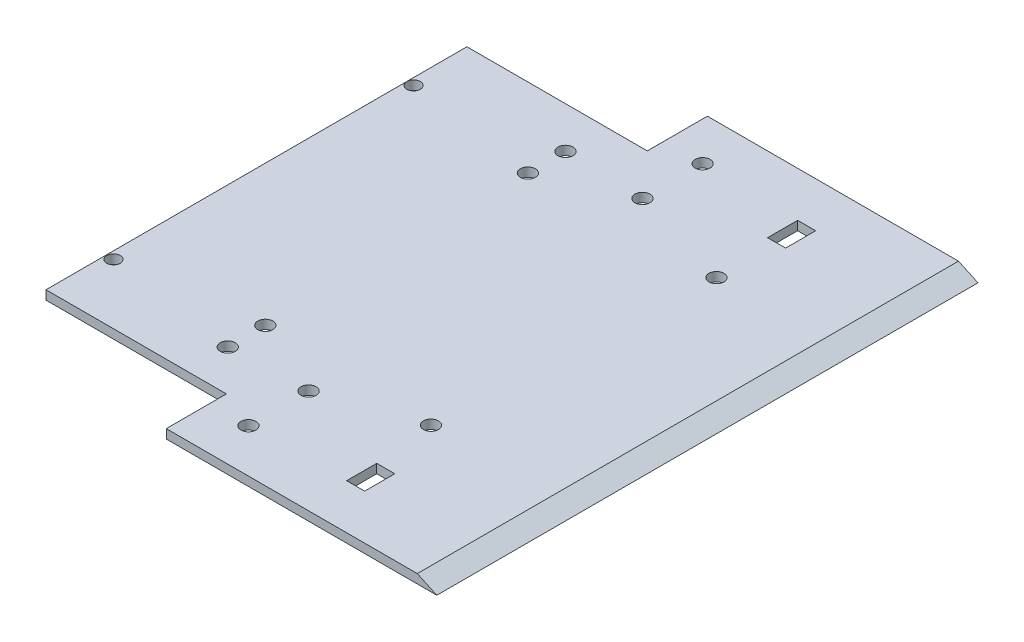
SolidWorks part; units mm, degrees
ref_plane "Front Plane" through (0, 0, 0) normal (0, 0, 1) x (1, 0, 0)
ref_plane "Top Plane" through (0, 0, 0) normal (0, 1, 0) x (1, 0, 0)
ref_plane "Right Plane" through (0, 0, 0) normal (1, 0, 0) x (0, 0, -1)
sketch "Esquisse1" plane through (0, 0, 0) normal (0, 1, 0) x (1, 0, 0)
  line L0 (-75, 0) -> (75, 0) construction
  line L1 (75, -90) -> (-75, -90)
  line L2 (75, -90) -> (75, 90)
  line L3 (75, 90) -> (-75, 90)
  line L4 (-75, -90) -> (-75, 90)
  line L5 (75, -90) -> (-75, 90) construction
  line L6 (75, 90) -> (-75, -90) construction
  line L7 (-75, 90) -> (-15, 90)
  line L8 (-75, 90) -> (-75, 70)
  line L9 (-75, 70) -> (-15, 70)
  line L10 (-15, 90) -> (-15, 70)
  line L11 (-75, -70) -> (-15, -70)
  line L12 (-15, -90) -> (-15, -70)
  line L13 (-75, -90) -> (-15, -90)
  line L14 (-75, -90) -> (-75, -70)
  line L15 (-2.1116, 55.5) -> (-2.1615, -75.5) construction
  line L16 (45, 90) -> (45, -90) construction
  line L17 (45, 0) -> (75, 0) construction
  line L18 (45, 0) -> (75, 90) construction
  line L19 (45, 90) -> (75, 0) construction
  line L20 (75, 0) -> (45, -90) construction
  line L21 (75, -90) -> (45, 0) construction
  line L22 (33, 90) -> (33, 70) construction
  line L23 (33, 70) -> (75, 70) construction
  line L24 (36, -65) -> (36, -75)
  line L25 (36, 65) -> (30, 65)
  line L26 (36, 65) -> (36, 75)
  line L27 (36, 75) -> (30, 75)
  line L28 (30, 65) -> (30, 75)
  line L29 (36, 65) -> (30, 75) construction
  line L30 (36, 75) -> (30, 65) construction
  line L31 (36, -75) -> (30, -75)
  line L32 (30, -65) -> (30, -75)
  line L33 (36, -65) -> (30, -65)
  circle A0 centre (-2.1116, 55.5) radius 2.5
  circle A1 centre (-2.1116, 75.5) radius 2.5
  circle A2 centre (-2.1615, -55.5) radius 2.5
  circle A3 centre (-2.1615, -75.5) radius 2.5
  circle A7 centre (33, 45) radius 2.5
  circle A8 centre (28.0394, -45) radius 2.5005
  circle A15 centre (-28.4765, 56.25) radius 2.5
  circle A16 centre (-28.4765, 43.75) radius 2.5
  circle A17 centre (-72.731, 50) radius 2.25
  circle A18 centre (-28.2769, -56.2709) radius 2.5
  circle A19 centre (-28.2769, -43.7709) radius 2.5
  circle A20 centre (-72.5314, -50.0209) radius 2.25
  point P0 (0, 0)
  dimension "D5" = 5
  dimension "D6" = 5
  dimension "D8" = 5
  dimension "D9" = 20
  dimension "D1" = 150
  dimension "D2" = 180
  dimension "D3" = 60
  dimension "D4" = 20
  dimension "D7" = 30
  dimension "D10" = 42
  dimension "D11" = 10
  dimension "D12" = 6
extrude "Boss.-Extru.1" add sketch "Esquisse1" along normal blind 3 contours L12 L1 L2 L3 L10 L9 L4 L11
sketch "Esquisse4" plane through (0, 0, 90) normal (0, 0, 1) x (1, 0, 0)
  line L2 (75, 3) -> (-15, 3) construction
  line L3 (68.506, 3) -> (75, 0)
  line L4 (68.506, 3) -> (76.0394, 3)
  line L5 (76.0394, 3) -> (83.3033, 0)
  line L6 (83.3033, 0) -> (75, 0)
extrude "Enlèv. mat.-Extru.2" cut sketch "Esquisse4" against normal blind 216
sketch "Esquisse5" plane through (0, 3, 0) normal (0, 1, 0) x (1, 0, 0)
  line L0 (-48.6921, 70) -> (-48.6921, 64.5) construction
  line L1 (-75, 70) -> (-15, 70) construction
  line L2 (-57.0445, 64.5) -> (-38.1964, 64.5)
  line L3 (-45, -70) -> (-45, -64.5) construction
  line L4 (-75, -70) -> (-15, -70) construction
  line L5 (-57.0445, -64.5) -> (-31.0518, -64.5)
  dimension "D1" = 5.5
  dimension "D2" = 5.5
sketch "Esquisse6" plane through (0, 0, 0) normal (0, -1, 0) x (1, 0, 0)
  line L0 (30, 90) -> (30, 70.5612) construction
  line L1 (75, 90) -> (-15, 90) construction
  line L2 (30, 70.5612) -> (75, 70.5612) construction
  line L3 (75, 90) -> (75, -90) construction
  dimension "D1" = 45
